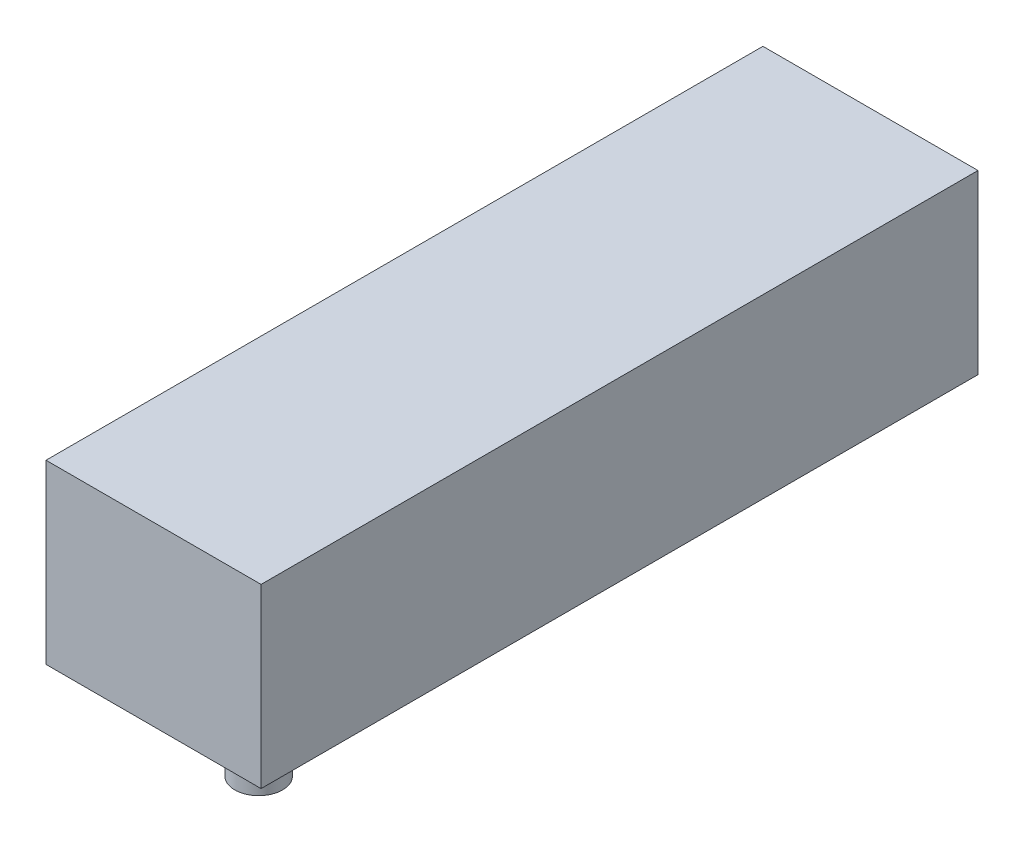
SolidWorks part; units mm, degrees
ref_plane "Front Plane" through (0, 0, 0) normal (0, 0, 1) x (1, 0, 0)
ref_plane "Top Plane" through (0, 0, 0) normal (0, 1, 0) x (1, 0, 0)
ref_plane "Right Plane" through (0, 0, 0) normal (1, 0, 0) x (0, 0, -1)
sketch "Sketch1" plane through (0, 0, 0) normal (0, 1, 0) x (1, 0, 0)
  line L1 (-9.5954, -64.3057) -> (12.9046, -64.3057)
  line L2 (-9.5954, -64.3057) -> (-9.5954, 10.6943)
  line L3 (-9.5954, 10.6943) -> (12.9046, 10.6943)
  line L4 (12.9046, -64.3057) -> (12.9046, 10.6943)
  dimension "D1" = 22.5
  dimension "D2" = 75
extrude "Boss-Extrude1" add sketch "Sketch1" along normal blind 18.5
sketch "Sketch2" plane through (0, 0, 0) normal (0, -1, 0) x (-1, 0, 0)
  line L0 (9.5954, -64.3057) -> (-12.9046, -64.3057) construction
  line L1 (9.5954, 10.6943) -> (9.5954, -64.3057) construction
  circle A0 centre (-1.6546, -53.3057) radius 2.5
  point P6 (6.4036, -53.4918)
  dimension "D1" = 5
  dimension "D2" = 11
  dimension "D3" = 11.25
extrude "Boss-Extrude2" add sketch "Sketch2" along normal blind 10
